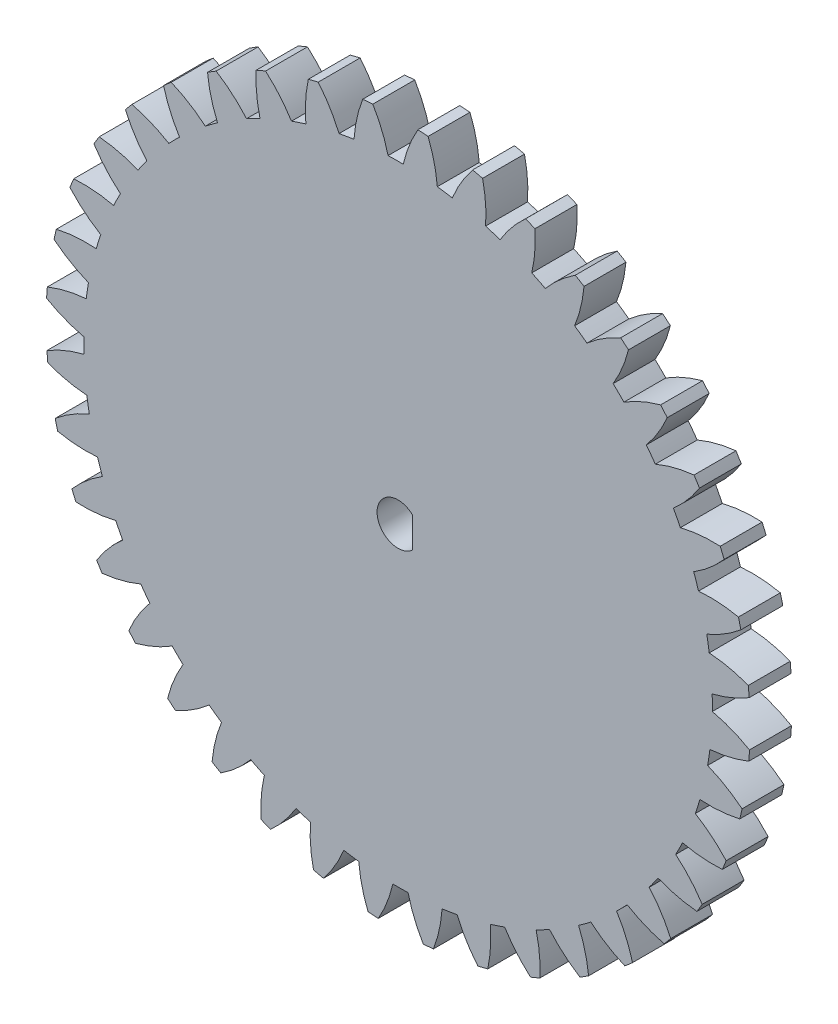
SolidWorks part; units mm, degrees
ref_plane "Front Plane" through (0, 0, 0) normal (0, 0, 1) x (1, 0, 0)
ref_plane "Top Plane" through (0, 0, 0) normal (0, 1, 0) x (1, 0, 0)
ref_plane "Right Plane" through (0, 0, 0) normal (1, 0, 0) x (0, 0, -1)
sketch "Sketch1" plane through (0, 0, 0) normal (0, 0, 1) x (1, 0, 0)
  arc B0 (-53.2553, 3.0046) -> (-47.6173, 0.7826) centre (-43.069, 20.587) ccw
  arc B1 (-47.6173, 0.7826) -> (-47.5997, -1.5139) centre (0, 0) ccw
  arc B2 (-47.5997, -1.5139) -> (-53.2029, -3.8222) centre (-42.7477, -21.2461) ccw
  arc B3 (-53.2029, -3.8222) -> (-53.0697, -5.3634) centre (0, 0) ccw
  arc B4 (-53.0697, -5.3634) -> (-47.1535, -6.676) centre (-45.7593, 13.5961) ccw
  arc B5 (-47.1535, -6.676) -> (-46.7768, -8.9415) centre (0, 0) ccw
  arc B6 (-46.7768, -8.9415) -> (-51.9499, -12.0979) centre (-38.8978, -27.6718) ccw
  arc B7 (-51.9499, -12.0979) -> (-51.5773, -13.5993) centre (0, 0) ccw
  arc B8 (-51.5773, -13.5993) -> (-45.5286, -13.9703) centre (-47.3228, 6.2704) ccw
  arc B9 (-45.5286, -13.9703) -> (-44.8022, -16.1489) centre (0, 0) ccw
  arc B10 (-44.8022, -16.1489) -> (-49.4178, -20.0758) centre (-34.0901, -33.416) ccw
  arc B11 (-49.4178, -20.0758) -> (-48.8149, -21.5003) centre (0, 0) ccw
  arc B12 (-48.8149, -21.5003) -> (-42.7826, -20.9205) centre (-47.7211, -1.2098) ccw
  arc B13 (-42.7826, -20.9205) -> (-41.7243, -22.9587) centre (0, 0) ccw
  arc B14 (-41.7243, -22.9587) -> (-45.6688, -27.5592) centre (-28.4429, -38.3375) ccw
  arc B15 (-45.6688, -27.5592) -> (-44.8505, -28.8719) centre (0, 0) ccw
  arc B16 (-44.8505, -28.8719) -> (-38.9832, -27.3556) centre (-46.9443, -8.6601) ccw
  arc B17 (-38.9832, -27.3556) -> (-37.6191, -29.2031) centre (0, 0) ccw
  arc B18 (-37.6191, -29.2031) -> (-40.7954, -34.3641) centre (-22.0955, -42.3149) ccw
  arc B19 (-40.7954, -34.3641) -> (-39.7818, -35.5326) centre (0, 0) ccw
  arc B20 (-39.7818, -35.5326) -> (-34.2239, -33.1172) centre (-45.0116, -15.8972) ccw
  arc B21 (-34.2239, -33.1172) -> (-32.5876, -34.7285) centre (0, 0) ccw
  arc B22 (-32.5876, -34.7285) -> (-34.9174, -40.3228) centre (-15.2039, -45.2505) ccw
  arc B23 (-34.9174, -40.3228) -> (-33.7334, -41.3184) centre (0, 0) ccw
  arc B24 (-33.7334, -41.3184) -> (-28.6219, -38.0632) centre (-41.9706, -22.7428) ccw
  arc B25 (-28.6219, -38.0632) -> (-26.7536, -39.3988) centre (0, 0) ccw
  arc B26 (-26.7536, -39.3988) -> (-28.1796, -45.2887) centre (-7.938, -47.0718) ccw
  arc B27 (-28.1796, -45.2887) -> (-26.8545, -46.0868) centre (0, 0) ccw
  arc B28 (-26.8545, -46.0868) -> (-22.3151, -42.072) centre (-37.8961, -29.0284) ccw
  arc B29 (-22.3151, -42.072) -> (-20.2609, -43.0989) centre (0, 0) ccw
  arc B30 (-20.2609, -43.0989) -> (-20.748, -49.1394) centre (-0.4766, -47.734) ccw
  arc B31 (-20.748, -49.1394) -> (-19.3143, -49.7203) centre (0, 0) ccw
  arc B32 (-19.3143, -49.7203) -> (-15.4588, -45.0449) centre (-32.8885, -34.5993) ccw
  arc B33 (-15.4588, -45.0449) -> (-13.2693, -45.7378) centre (0, 0) ccw
  arc B34 (-13.2693, -45.7378) -> (-12.8054, -51.7801) centre (6.9965, -47.2209) ccw
  arc B35 (-12.8054, -51.7801) -> (-11.2986, -52.1296) centre (0, 0) ccw
  arc B36 (-11.2986, -52.1296) -> (-8.2219, -46.9086) centre (-27.071, -39.3182) ccw
  arc B37 (-8.2219, -46.9086) -> (-5.951, -47.2505) centre (0, 0) ccw
  arc B38 (-5.951, -47.2505) -> (-4.5476, -53.1458) centre (14.2973, -45.545) ccw
  arc B39 (-4.5476, -53.1458) -> (-3.0046, -53.2553) centre (0, 0) ccw
  arc B40 (-3.0046, -53.2553) -> (-0.7826, -47.6173) centre (-20.587, -43.069) ccw
  arc B41 (-0.7826, -47.6173) -> (1.5139, -47.5997) centre (0, 0) ccw
  arc B42 (1.5139, -47.5997) -> (3.8222, -53.2029) centre (21.2461, -42.7477) ccw
  arc B43 (3.8222, -53.2029) -> (5.3634, -53.0697) centre (0, 0) ccw
  arc B44 (5.3634, -53.0697) -> (6.676, -47.1535) centre (-13.5961, -45.7593) ccw
  arc B45 (6.676, -47.1535) -> (8.9415, -46.7768) centre (0, 0) ccw
  arc B46 (8.9415, -46.7768) -> (12.0979, -51.9499) centre (27.6718, -38.8978) ccw
  arc B47 (12.0979, -51.9499) -> (13.5993, -51.5773) centre (0, 0) ccw
  arc B48 (13.5993, -51.5773) -> (13.9703, -45.5286) centre (-6.2704, -47.3228) ccw
  arc B49 (13.9703, -45.5286) -> (16.1489, -44.8022) centre (0, 0) ccw
  arc B50 (16.1489, -44.8022) -> (20.0758, -49.4178) centre (33.416, -34.0901) ccw
  arc B51 (20.0758, -49.4178) -> (21.5003, -48.8149) centre (0, 0) ccw
  arc B52 (21.5003, -48.8149) -> (20.9205, -42.7826) centre (1.2098, -47.7211) ccw
  arc B53 (20.9205, -42.7826) -> (22.9587, -41.7243) centre (0, 0) ccw
  arc B54 (22.9587, -41.7243) -> (27.5592, -45.6688) centre (38.3375, -28.4429) ccw
  arc B55 (27.5592, -45.6688) -> (28.8719, -44.8505) centre (0, 0) ccw
  arc B56 (28.8719, -44.8505) -> (27.3556, -38.9832) centre (8.6601, -46.9443) ccw
  arc B57 (27.3556, -38.9832) -> (29.2031, -37.6191) centre (0, 0) ccw
  arc B58 (29.2031, -37.6191) -> (34.3641, -40.7954) centre (42.3149, -22.0955) ccw
  arc B59 (34.3641, -40.7954) -> (35.5326, -39.7818) centre (0, 0) ccw
  arc B60 (35.5326, -39.7818) -> (33.1172, -34.2239) centre (15.8972, -45.0116) ccw
  arc B61 (33.1172, -34.2239) -> (34.7285, -32.5876) centre (0, 0) ccw
  arc B62 (34.7285, -32.5876) -> (40.3228, -34.9174) centre (45.2505, -15.2039) ccw
  arc B63 (40.3228, -34.9174) -> (41.3184, -33.7334) centre (0, 0) ccw
  arc B64 (41.3184, -33.7334) -> (38.0632, -28.6219) centre (22.7428, -41.9706) ccw
  arc B65 (38.0632, -28.6219) -> (39.3988, -26.7536) centre (0, 0) ccw
  arc B66 (39.3988, -26.7536) -> (45.2887, -28.1796) centre (47.0718, -7.938) ccw
  arc B67 (45.2887, -28.1796) -> (46.0868, -26.8545) centre (0, 0) ccw
  arc B68 (46.0868, -26.8545) -> (42.072, -22.3151) centre (29.0284, -37.8961) ccw
  arc B69 (42.072, -22.3151) -> (43.0989, -20.2609) centre (0, 0) ccw
  arc B70 (43.0989, -20.2609) -> (49.1394, -20.748) centre (47.734, -0.4766) ccw
  arc B71 (49.1394, -20.748) -> (49.7203, -19.3143) centre (0, 0) ccw
  arc B72 (49.7203, -19.3143) -> (45.0449, -15.4588) centre (34.5993, -32.8885) ccw
  arc B73 (45.0449, -15.4588) -> (45.7378, -13.2693) centre (0, 0) ccw
  arc B74 (45.7378, -13.2693) -> (51.7801, -12.8054) centre (47.2209, 6.9965) ccw
  arc B75 (51.7801, -12.8054) -> (52.1296, -11.2986) centre (0, 0) ccw
  arc B76 (52.1296, -11.2986) -> (46.9086, -8.2219) centre (39.3182, -27.071) ccw
  arc B77 (46.9086, -8.2219) -> (47.2505, -5.951) centre (0, 0) ccw
  arc B78 (47.2505, -5.951) -> (53.1458, -4.5476) centre (45.545, 14.2973) ccw
  arc B79 (53.1458, -4.5476) -> (53.2553, -3.0046) centre (0, 0) ccw
  arc B80 (53.2553, -3.0046) -> (47.6173, -0.7826) centre (43.069, -20.587) ccw
  arc B81 (47.6173, -0.7826) -> (47.5997, 1.5139) centre (0, 0) ccw
  arc B82 (47.5997, 1.5139) -> (53.2029, 3.8222) centre (42.7477, 21.2461) ccw
  arc B83 (53.2029, 3.8222) -> (53.0697, 5.3634) centre (0, 0) ccw
  arc B84 (53.0697, 5.3634) -> (47.1535, 6.676) centre (45.7593, -13.5961) ccw
  arc B85 (47.1535, 6.676) -> (46.7768, 8.9415) centre (0, 0) ccw
  arc B86 (46.7768, 8.9415) -> (51.9499, 12.0979) centre (38.8978, 27.6718) ccw
  arc B87 (51.9499, 12.0979) -> (51.5773, 13.5993) centre (0, 0) ccw
  arc B88 (51.5773, 13.5993) -> (45.5286, 13.9703) centre (47.3228, -6.2704) ccw
  arc B89 (45.5286, 13.9703) -> (44.8022, 16.1489) centre (0, 0) ccw
  arc B90 (44.8022, 16.1489) -> (49.4178, 20.0758) centre (34.0901, 33.416) ccw
  arc B91 (49.4178, 20.0758) -> (48.8149, 21.5003) centre (0, 0) ccw
  arc B92 (48.8149, 21.5003) -> (42.7826, 20.9205) centre (47.7211, 1.2098) ccw
  arc B93 (42.7826, 20.9205) -> (41.7243, 22.9587) centre (0, 0) ccw
  arc B94 (41.7243, 22.9587) -> (45.6688, 27.5592) centre (28.4429, 38.3375) ccw
  arc B95 (45.6688, 27.5592) -> (44.8505, 28.8719) centre (0, 0) ccw
  arc B96 (44.8505, 28.8719) -> (38.9832, 27.3556) centre (46.9443, 8.6601) ccw
  arc B97 (38.9832, 27.3556) -> (37.6191, 29.2031) centre (0, 0) ccw
  arc B98 (37.6191, 29.2031) -> (40.7954, 34.3641) centre (22.0955, 42.3149) ccw
  arc B99 (40.7954, 34.3641) -> (39.7818, 35.5326) centre (0, 0) ccw
  arc B100 (39.7818, 35.5326) -> (34.2239, 33.1172) centre (45.0116, 15.8972) ccw
  arc B101 (34.2239, 33.1172) -> (32.5876, 34.7285) centre (0, 0) ccw
  arc B102 (32.5876, 34.7285) -> (34.9174, 40.3228) centre (15.2039, 45.2505) ccw
  arc B103 (34.9174, 40.3228) -> (33.7334, 41.3184) centre (0, 0) ccw
  arc B104 (33.7334, 41.3184) -> (28.6219, 38.0632) centre (41.9706, 22.7428) ccw
  arc B105 (28.6219, 38.0632) -> (26.7536, 39.3988) centre (0, 0) ccw
  arc B106 (26.7536, 39.3988) -> (28.1796, 45.2887) centre (7.938, 47.0718) ccw
  arc B107 (28.1796, 45.2887) -> (26.8545, 46.0868) centre (0, 0) ccw
  arc B108 (26.8545, 46.0868) -> (22.3151, 42.072) centre (37.8961, 29.0284) ccw
  arc B109 (22.3151, 42.072) -> (20.2609, 43.0989) centre (0, 0) ccw
  arc B110 (20.2609, 43.0989) -> (20.748, 49.1394) centre (0.4766, 47.734) ccw
  arc B111 (20.748, 49.1394) -> (19.3143, 49.7203) centre (0, 0) ccw
  arc B112 (19.3143, 49.7203) -> (15.4588, 45.0449) centre (32.8885, 34.5993) ccw
  arc B113 (15.4588, 45.0449) -> (13.2693, 45.7378) centre (0, 0) ccw
  arc B114 (13.2693, 45.7378) -> (12.8054, 51.7801) centre (-6.9965, 47.2209) ccw
  arc B115 (12.8054, 51.7801) -> (11.2986, 52.1296) centre (0, 0) ccw
  arc B116 (11.2986, 52.1296) -> (8.2219, 46.9086) centre (27.071, 39.3182) ccw
  arc B117 (8.2219, 46.9086) -> (5.951, 47.2505) centre (0, 0) ccw
  arc B118 (5.951, 47.2505) -> (4.5476, 53.1458) centre (-14.2973, 45.545) ccw
  arc B119 (4.5476, 53.1458) -> (3.0046, 53.2553) centre (0, 0) ccw
  arc B120 (3.0046, 53.2553) -> (0.7826, 47.6173) centre (20.587, 43.069) ccw
  arc B121 (0.7826, 47.6173) -> (-1.5139, 47.5997) centre (0, 0) ccw
  arc B122 (-1.5139, 47.5997) -> (-3.8222, 53.2029) centre (-21.2461, 42.7477) ccw
  arc B123 (-3.8222, 53.2029) -> (-5.3634, 53.0697) centre (0, 0) ccw
  arc B124 (-5.3634, 53.0697) -> (-6.676, 47.1535) centre (13.5961, 45.7593) ccw
  arc B125 (-6.676, 47.1535) -> (-8.9415, 46.7768) centre (0, 0) ccw
  arc B126 (-8.9415, 46.7768) -> (-12.0979, 51.9499) centre (-27.6718, 38.8978) ccw
  arc B127 (-12.0979, 51.9499) -> (-13.5993, 51.5773) centre (0, 0) ccw
  arc B128 (-13.5993, 51.5773) -> (-13.9703, 45.5286) centre (6.2704, 47.3228) ccw
  arc B129 (-13.9703, 45.5286) -> (-16.1489, 44.8022) centre (0, 0) ccw
  arc B130 (-16.1489, 44.8022) -> (-20.0758, 49.4178) centre (-33.416, 34.0901) ccw
  arc B131 (-20.0758, 49.4178) -> (-21.5003, 48.8149) centre (0, 0) ccw
  arc B132 (-21.5003, 48.8149) -> (-20.9205, 42.7826) centre (-1.2098, 47.7211) ccw
  arc B133 (-20.9205, 42.7826) -> (-22.9587, 41.7243) centre (0, 0) ccw
  arc B134 (-22.9587, 41.7243) -> (-27.5592, 45.6688) centre (-38.3375, 28.4429) ccw
  arc B135 (-27.5592, 45.6688) -> (-28.8719, 44.8505) centre (0, 0) ccw
  arc B136 (-28.8719, 44.8505) -> (-27.3556, 38.9832) centre (-8.6601, 46.9443) ccw
  arc B137 (-27.3556, 38.9832) -> (-29.2031, 37.6191) centre (0, 0) ccw
  arc B138 (-29.2031, 37.6191) -> (-34.3641, 40.7954) centre (-42.3149, 22.0955) ccw
  arc B139 (-34.3641, 40.7954) -> (-35.5326, 39.7818) centre (0, 0) ccw
  arc B140 (-35.5326, 39.7818) -> (-33.1172, 34.2239) centre (-15.8972, 45.0116) ccw
  arc B141 (-33.1172, 34.2239) -> (-34.7285, 32.5876) centre (0, 0) ccw
  arc B142 (-34.7285, 32.5876) -> (-40.3228, 34.9174) centre (-45.2505, 15.2039) ccw
  arc B143 (-40.3228, 34.9174) -> (-41.3184, 33.7334) centre (0, 0) ccw
  arc B144 (-41.3184, 33.7334) -> (-38.0632, 28.6219) centre (-22.7428, 41.9706) ccw
  arc B145 (-38.0632, 28.6219) -> (-39.3988, 26.7536) centre (0, 0) ccw
  arc B146 (-39.3988, 26.7536) -> (-45.2887, 28.1796) centre (-47.0718, 7.938) ccw
  arc B147 (-45.2887, 28.1796) -> (-46.0868, 26.8545) centre (0, 0) ccw
  arc B148 (-46.0868, 26.8545) -> (-42.072, 22.3151) centre (-29.0284, 37.8961) ccw
  arc B149 (-42.072, 22.3151) -> (-43.0989, 20.2609) centre (0, 0) ccw
  arc B150 (-43.0989, 20.2609) -> (-49.1394, 20.748) centre (-47.734, 0.4766) ccw
  arc B151 (-49.1394, 20.748) -> (-49.7203, 19.3143) centre (0, 0) ccw
  arc B152 (-49.7203, 19.3143) -> (-45.0449, 15.4588) centre (-34.5993, 32.8885) ccw
  arc B153 (-45.0449, 15.4588) -> (-45.7378, 13.2693) centre (0, 0) ccw
  arc B154 (-45.7378, 13.2693) -> (-51.7801, 12.8054) centre (-47.2209, -6.9965) ccw
  arc B155 (-51.7801, 12.8054) -> (-52.1296, 11.2986) centre (0, 0) ccw
  arc B156 (-52.1296, 11.2986) -> (-46.9086, 8.2219) centre (-39.3182, 27.071) ccw
  arc B157 (-46.9086, 8.2219) -> (-47.2505, 5.951) centre (0, 0) ccw
  arc B158 (-47.2505, 5.951) -> (-53.1458, 4.5476) centre (-45.545, -14.2973) ccw
  arc B159 (-53.1458, 4.5476) -> (-53.2553, 3.0046) centre (0, 0) ccw
sketch_block_instance "Center_Gear-1"
sketch_block "Center_Gear"
extrude "Boss-Extrude1" add sketch "Sketch1" along normal blind 6.35
sketch "Sketch2" plane through (0, 0, 6.35) normal (0, 0, 1) x (1, 0, 0)
  line L0 (1.5, 2.5981) -> (1.5, -2.5981)
  arc A0 (1.5, 2.5981) -> (1.5, -2.5981) centre (0, 0) ccw
  dimension "D1" = 6
  dimension "D2" = 1.5
extrude "Cut-Extrude1" [suppressed] cut sketch "Sketch2" against normal up to next
sketch "Sketch3" plane through (0, 0, 6.35) normal (0, 0, 1) x (1, 0, 0)
  line L0 (2.1828, 2.3056) -> (2.1828, -2.3056)
  arc A0 (2.1828, 2.3056) -> (2.1828, -2.3056) centre (0, 0) ccw
  dimension "D1" = 6.35
  dimension "D2" = 2.1828
extrude "Cut-Extrude2" cut sketch "Sketch3" against normal up to next
